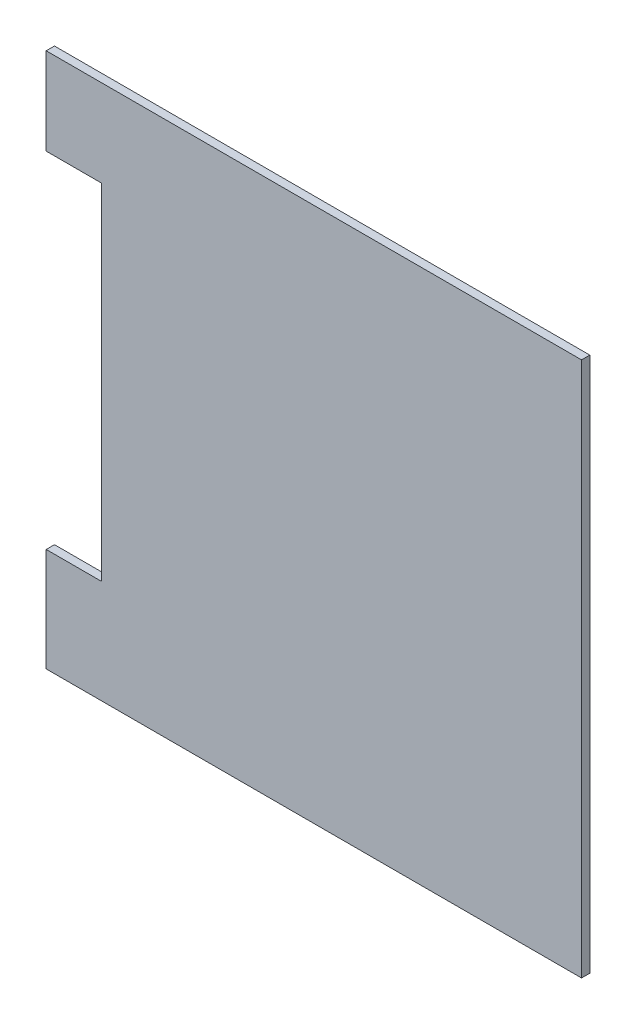
SolidWorks part; units mm, degrees
material "PET"
ref_plane "Front Plane" through (0, 0, 0) normal (0, 0, 1) x (1, 0, 0)
ref_plane "Top Plane" through (0, 0, 0) normal (0, 1, 0) x (1, 0, 0)
ref_plane "Right Plane" through (0, 0, 0) normal (1, 0, 0) x (0, 0, -1)
sketch "Sketch1" plane through (0, 0, 0) normal (0, 0, 1) x (1, 0, 0)
  line L1 (-28.5714, 365.1048) -> (359.4286, 365.1048)
  line L2 (-28.5714, 365.1048) -> (-28.5714, -22.8952)
  line L3 (-28.5714, -22.8952) -> (359.4286, -22.8952)
  line L4 (359.4286, 365.1048) -> (359.4286, -22.8952)
  dimension "D1" = 388
  dimension "D2" = 388
extrude "Boss-Extrude1" add sketch "Sketch1" along normal blind 6
sketch "Sketch2" plane through (0, 0, 6) normal (0, 0, 1) x (1, 0, 0)
  line L7 (-28.5714, -22.8952) -> (359.4286, -22.8952) construction
  line L8 (-28.5714, 302.1048) -> (11.4286, 302.1048)
  line L9 (-28.5714, 302.1048) -> (-28.5714, 52.1048)
  line L10 (-28.5714, 52.1048) -> (11.4286, 52.1048)
  line L11 (11.4286, 302.1048) -> (11.4286, 52.1048)
  line L12 (-28.5714, 365.1048) -> (-28.5714, -22.8952) construction
  dimension "D1" = 40
  dimension "D2" = 0
  dimension "D7" = 75
  dimension "D8" = 250
extrude "Cut-Extrude1" cut sketch "Sketch2" against normal blind 10
